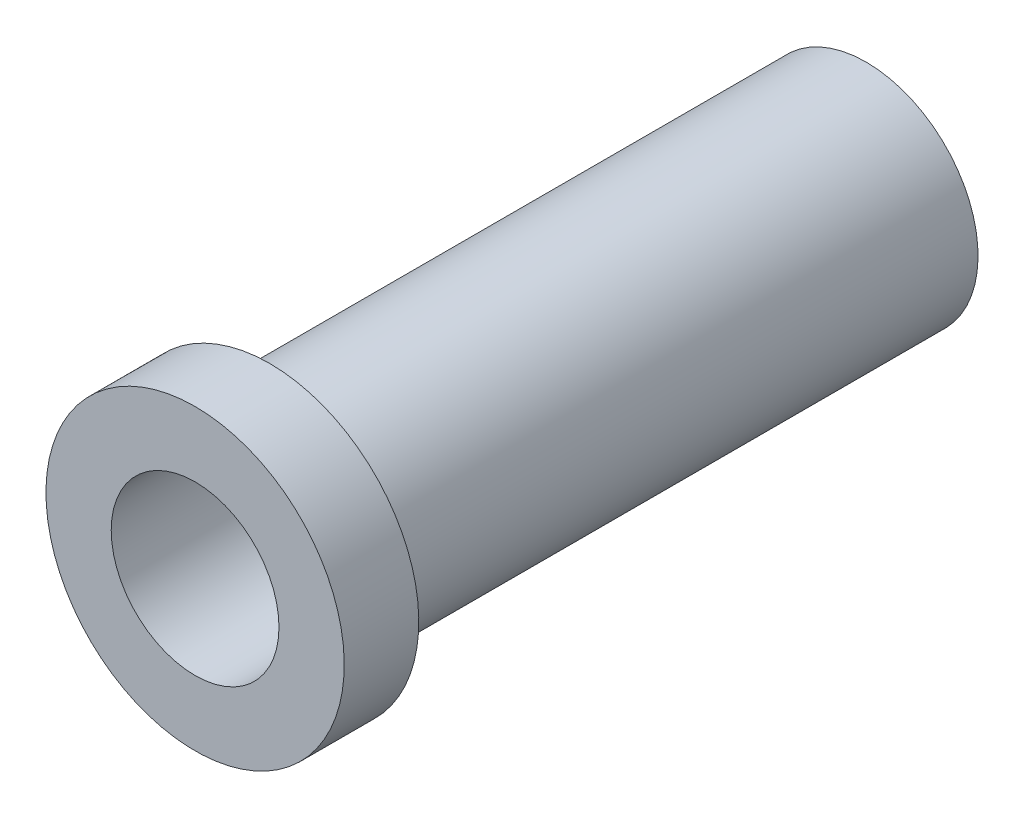
SolidWorks part; units mm, degrees
ref_plane "Front Plane" through (0, 0, 0) normal (0, 0, 1) x (1, 0, 0)
ref_plane "Top Plane" through (0, 0, 0) normal (0, 1, 0) x (1, 0, 0)
ref_plane "Right Plane" through (0, 0, 0) normal (1, 0, 0) x (0, 0, -1)
sketch "Sketch2" plane through (0, 0, 0) normal (1, 0, 0) x (0, 0, -1)
  line L0 (57.15, 0) -> (-57.15, 0)
  line L1 (-57.15, 0) -> (-57.15, -25.4)
  line L2 (-57.15, -25.4) -> (-44.45, -25.4)
  line L3 (-44.45, -25.4) -> (-44.45, -19.05)
  line L4 (-44.45, -19.05) -> (57.15, -19.05)
  line L5 (57.15, -19.05) -> (57.15, 0)
  point P3 (0, 0)
  dimension "D1" = 114.3
  dimension "D2" = 25.4
  dimension "D3" = 12.7
revolve "Revolve1" add sketch "Sketch2" angle 360 about L0
sketch "Sketch3" plane through (0, 0, 57.15) normal (0, 0, 1) x (1, 0, 0)
  circle A0 centre (0, 0) radius 14.2875
extrude "Cut-Extrude1" cut sketch "Sketch3" against normal blind 127
